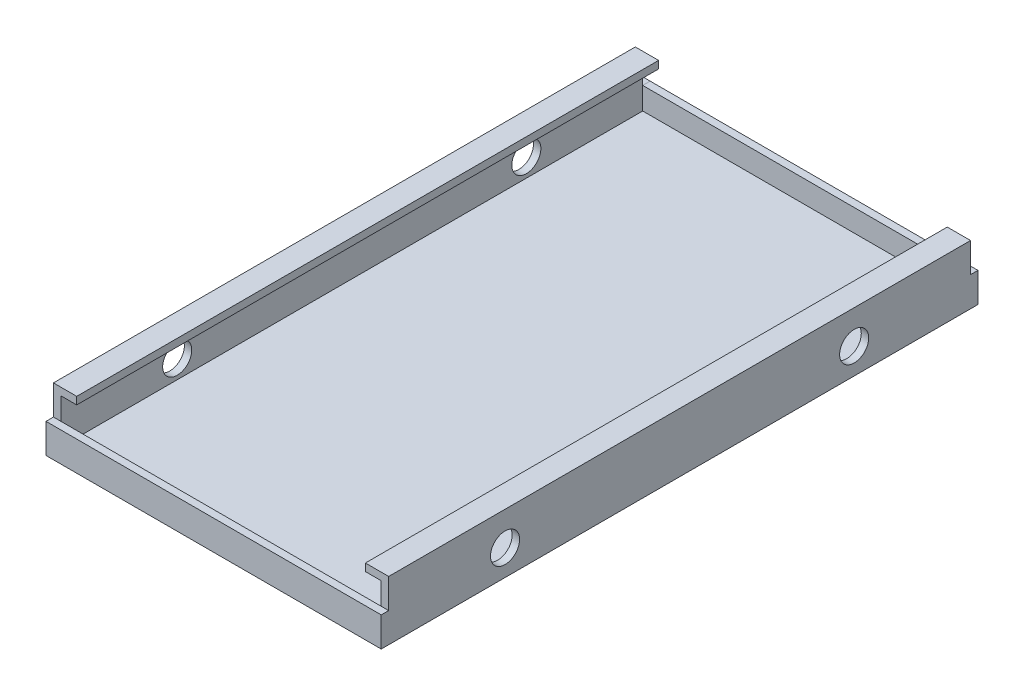
SolidWorks part; units mm, degrees
material "6061-T6 (SS)"
ref_plane "Front Plane" through (0, 0, 0) normal (0, 0, 1) x (1, 0, 0)
ref_plane "Top Plane" through (0, 0, 0) normal (0, 1, 0) x (1, 0, 0)
ref_plane "Right Plane" through (0, 0, 0) normal (1, 0, 0) x (0, 0, -1)
sketch "Sketch1" plane through (0, 0, 0) normal (0, 0, 1) x (1, 0, 0)
  line L0 (-69.85, 19.05) -> (-69.85, -19.0497)
  line L1 (-76.2, -25.4) -> (76.2, -25.4)
  line L2 (-76.2, -25.4) -> (-76.2, 19.05)
  line L11 (-69.85, 19.05) -> (-76.2, 19.05)
  line L12 (205.4655, 19.05) -> (211.8655, 19.05)
  line L13 (-69.85, -19.0497) -> (69.85, -19.0497)
  line L16 (76.2, -25.4) -> (211.8655, -25.4)
  line L17 (211.8655, -25.4) -> (211.8655, 19.05)
  line L18 (69.85, -19.0497) -> (205.4655, -19.0497)
  line L19 (205.4655, -19.0497) -> (205.4655, 19.05)
  point P0 (0, 0)
  point P6 (0, 0)
  dimension "D1" = 6.3503
  dimension "D2" = 152.4
  dimension "D3" = 6.35
  dimension "D4" = 38.0997
  dimension "D5" = 6.4
  dimension "D6" = 44.45
  dimension "D7" = 288.0655
extrude "Boss-Extrude1" add sketch "Sketch1" along normal blind 500
sketch "Sketch2" plane through (211.8655, 0, 0) normal (1, 0, 0) x (0, 0, -1)
  line L0 (-500, -3.175) -> (0, -3.175) construction
  line L5 (-500, -25.4) -> (0, -25.4) construction
  line L8 (-500, -25.4) -> (-500, 19.05) construction
  line L9 (0, -25.4) -> (0, 19.05) construction
  circle A0 centre (-400, -3.2) radius 12.5
  circle A1 centre (-100, -3.2) radius 12.5
  dimension "D1" = 22.2
  dimension "D2" = 22.2
extrude "Cut-Extrude1" cut sketch "Sketch2" against normal blind 485.648
sketch "Sketch3" plane through (211.8655, 0, 0) normal (1, 0, 0) x (0, 0, -1)
  line L0 (-500, 19.05) -> (-500, 25.45)
  line L1 (-500, 25.45) -> (0, 25.45)
  line L2 (0, 25.45) -> (0, 19.05)
  line L3 (0, 19.05) -> (-500, 19.05)
  dimension "D1" = 6.4
extrude "Boss-Extrude3" add sketch "Sketch3" against normal blind 20
sketch "Sketch4" plane through (-76.2, 0, 0) normal (-1, 0, 0) x (0, 0, 1)
  line L0 (0, 19.05) -> (0, 25.45)
  line L1 (0, 25.45) -> (500, 25.45) construction
  line L2 (0, 19.05) -> (0, 25.45) construction
  line L3 (0, 25.45) -> (500, 25.45)
  line L4 (500, 25.45) -> (500, 19.05)
  line L5 (500, 19.05) -> (0, 19.05)
extrude "Boss-Extrude4" add sketch "Sketch4" against normal blind 20
sketch "Sketch5" plane through (0, 0, 0) normal (0, 0, -1) x (-1, 0, 0)
  line L0 (-211.8655, -25.4) -> (76.2, -25.4)
  line L1 (-211.8655, -25.4) -> (-211.8655, -19.0587)
  line L2 (76.2, -25.4) -> (76.2, -19.0587)
  line L4 (76.2, -19.0587) -> (76.2, 0.025)
  line L5 (76.2, 25.45) -> (76.2, -25.4) construction
  line L6 (76.2, 0.025) -> (69.85, 0.0001)
  line L7 (69.85, -19.0497) -> (69.85, 19.05) construction
  line L11 (-205.4655, 19.05) -> (-205.4655, -19.0497) construction
  line L12 (-205.4655, 0.0001) -> (-211.8655, 0.025)
  line L13 (-211.8655, -25.4) -> (-211.8655, 25.45) construction
  line L14 (-211.8655, 0.025) -> (-211.8655, -19.0587)
  line L15 (-205.4655, 0.0001) -> (69.85, 0.0001)
extrude "Boss-Extrude5" add sketch "Sketch5" along normal blind 6.4
sketch "Sketch6" plane through (0, 0, 500) normal (0, 0, 1) x (1, 0, 0)
  line L0 (-76.2, -25.4) -> (-76.2, 0.025)
  line L1 (-76.2, 25.45) -> (-76.2, -25.4) construction
  line L2 (-76.2, 0.025) -> (211.8655, 0.025)
  line L3 (211.8655, -25.4) -> (211.8655, 25.45) construction
  line L4 (211.8655, 0.025) -> (211.8655, -25.4)
  line L5 (211.8655, -25.4) -> (-76.2, -25.4)
  point P5 (-76.2, -12.6875)
  dimension "D1" = 288.0655
  dimension "D2" = 25.425
extrude "Boss-Extrude6" add sketch "Sketch6" along normal blind 6.4
